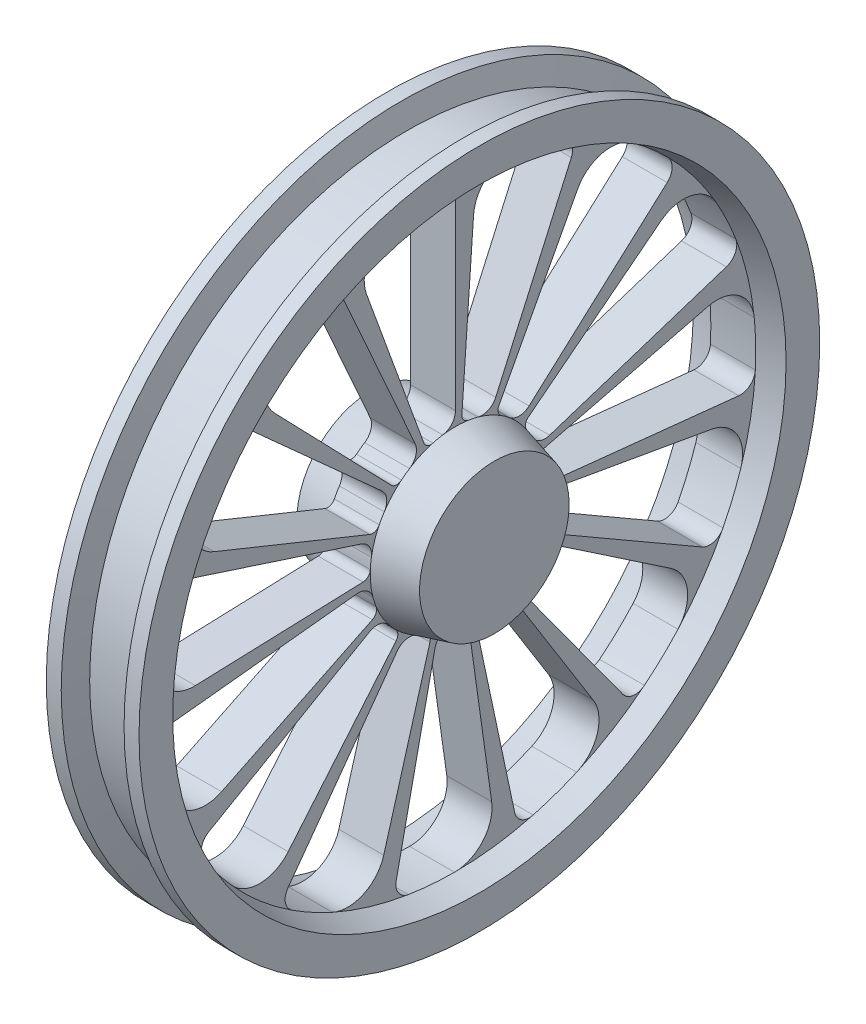
SolidWorks part; units mm, degrees
material "Alliage 1060"
ref_plane "Plan de face" through (0, 0, 0) normal (0, 0, 1) x (1, 0, 0)
ref_plane "Plan de dessus" through (0, 0, 0) normal (0, 1, 0) x (1, 0, 0)
ref_plane "Plan de droite" through (0, 0, 0) normal (1, 0, 0) x (0, 0, -1)
sketch "Esquisse1" plane through (0, 0, 0) normal (0, 1, 0) x (1, 0, 0)
  line L1 (-60, 113.9334) -> (-60, 401.4256)
  line L2 (-60, 401.4256) -> (-92, 410)
  line L3 (-92, 410) -> (-92, 455)
  line L12 (0, 401.4256) -> (0, 113.9334)
  line L13 (-92, 455) -> (-72, 455)
  line L14 (-72, 455) -> (-63.9615, 425)
  line L15 (-63.9615, 425) -> (3.9615, 425)
  line L16 (3.9615, 425) -> (12, 455)
  line L17 (12, 455) -> (32, 455)
  line L18 (32, 455) -> (32, 410)
  line L20 (-60, 401.4256) -> (-83.5108, 401.4256) construction
  line L21 (0, 401.4256) -> (32, 410)
  line L22 (0, 401.4256) -> (20.2175, 401.4256) construction
  line L23 (-63.9615, 425) -> (-63.9615, 454.5338) construction
  line L24 (-63.9615, 450.3967) -> (3.9615, 425) construction
  line L25 (3.9615, 425) -> (3.9615, 450.3967) construction
  line L27 (-112, 0) -> (-112, 100)
  line L28 (-112, 100) -> (-60, 113.9334)
  line L30 (0, 113.9334) -> (52, 100)
  line L31 (52, 100) -> (52, 0)
  line L33 (-112, 113.9334) -> (-60, 113.9334) construction
  line L34 (0, 113.9334) -> (52, 113.9334) construction
  line L35 (52, 0) -> (-112, 0)
  dimension "D9" = 60
  dimension "D5" = 15
  dimension "D6" = 20
  dimension "D7" = 20
  dimension "D8" = 15
  dimension "D11" = 15
  dimension "D12" = 30
  dimension "D15" = 30
  dimension "D18" = 100
  dimension "D19" = 100
  dimension "D20" = 15
  dimension "D21" = 15
  dimension "D3" = 455
  dimension "D14" = 124
  dimension "D4" = 164
  dimension "D10" = 15
  dimension "D13" = 45
  dimension "D16" = 45
revolve "Révolution1" add sketch "Esquisse1" angle 360 about L35
sketch "Esquisse2" plane through (-60, 0, 0) normal (-1, 0, 0) x (0, 0, 1)
  line L0 (0, 0) -> (0, 401.4256) construction
  line L1 (0, 0) -> (137.2957, 377.2167) construction
  line L2 (118.9719, 326.8725) -> (42.2495, 116.0795)
  line L3 (0, 380.9009) -> (0, 132.4317)
  circle A0 centre (0, 0) radius 401.4256 construction
  arc A1 (30.2017, 109.8575) -> (17.0134, 112.6559) centre (0, 0) ccw
  circle A2 centre (0, 0) radius 113.9334 construction
  arc A3 (82.2294, 392.9133) -> (21.0487, 400.8734) centre (0, 0) ccw
  arc A4 (21.0487, 400.8734) -> (0, 380.9009) centre (20, 380.9009) ccw
  arc A5 (17.0134, 112.6559) -> (0, 132.4317) centre (20, 132.4317) cw
  arc A6 (118.9719, 326.8725) -> (82.2294, 392.9133) centre (71.9872, 343.9736) ccw
  arc A7 (30.2017, 109.8575) -> (42.2495, 116.0795) centre (32.8526, 119.4997) ccw
  point P16 (0, 113.9334)
  point P22 (38.9675, 107.0623)
  dimension "D2" = 20
  dimension "D3" = 20
  dimension "D4" = 50
  dimension "D5" = 10
  dimension "D1" = 20
extrude "Enlèv. mat.-Extru.1" cut sketch "Esquisse2" against normal through all
pattern_circular "Répétition circulaire2" count 15 over 360 about axis through (0, 0, 0) along (1, 0, 0) of "Enlèv. mat.-Extru.1"
equation "\"a\"= 124"
equation "\"b\"= 910"
equation "\"D3@Esquisse1\"=\"b\"/2"
equation "\"D14@Esquisse1\"=\"a\""
equation "\"D4@Esquisse1\"=\"a\"+40"
